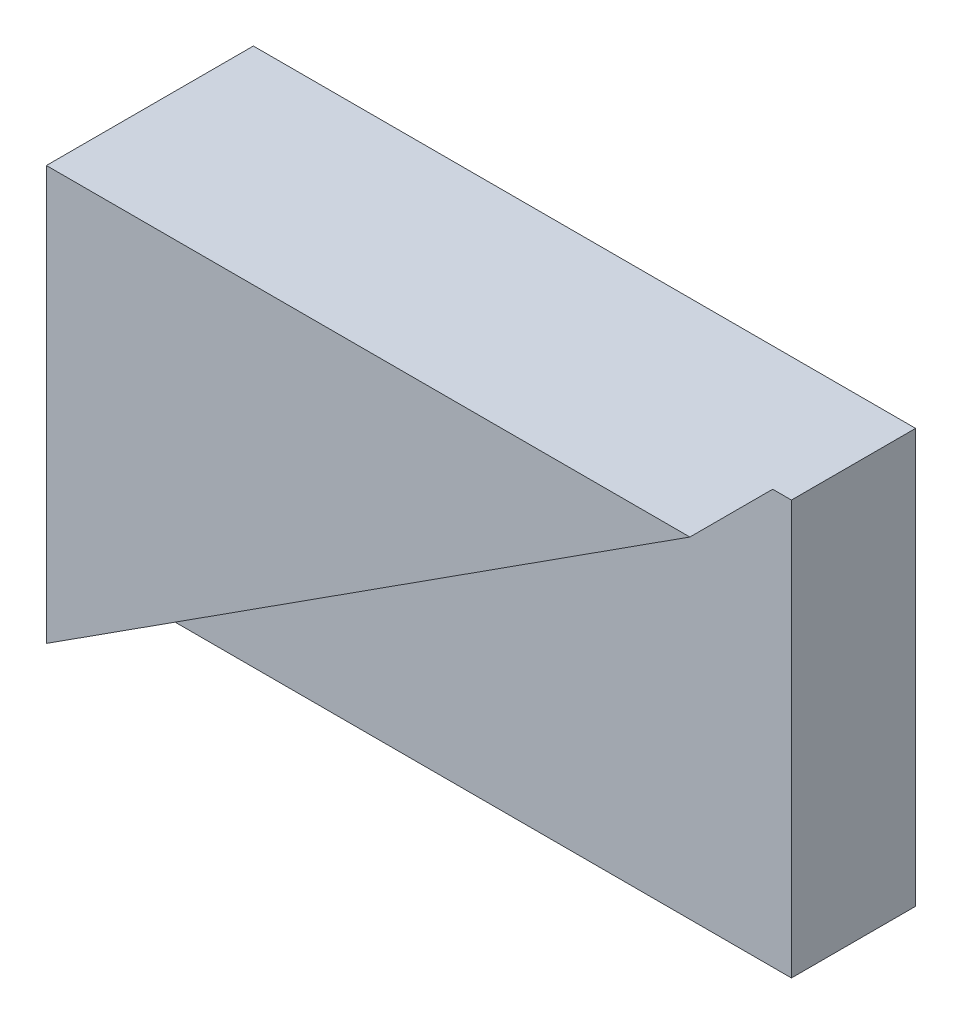
SolidWorks part; units mm, degrees
ref_plane "前视基准面" through (0, 0, 0) normal (0, 0, 1) x (1, 0, 0)
ref_plane "上视基准面" through (0, 0, 0) normal (0, 1, 0) x (1, 0, 0)
ref_plane "右视基准面" through (0, 0, 0) normal (1, 0, 0) x (0, 0, -1)
sketch "草图1" plane through (0, 0, 0) normal (0, 0, 1) x (1, 0, 0)
  line L1 (0, 0) -> (16, 0)
  line L2 (0, 0) -> (0, 10)
  line L3 (0, 10) -> (16, 10)
  line L4 (16, 0) -> (16, 10)
  dimension "D1" = 10
  dimension "D2" = 16
extrude "凸台-拉伸1" add sketch "草图1" along normal blind 5
sketch "草图2" plane through (0, 0, 5) normal (0, 0, 1) x (1, 0, 0)
  line L0 (0, 0) -> (16, 0)
  line L1 (16, 0) -> (16, 10.2915)
  line L2 (16, 10.2915) -> (0, 0)
  dimension "D1" = 32.75
extrude "切除-拉伸1" cut sketch "草图2" against normal blind 2
